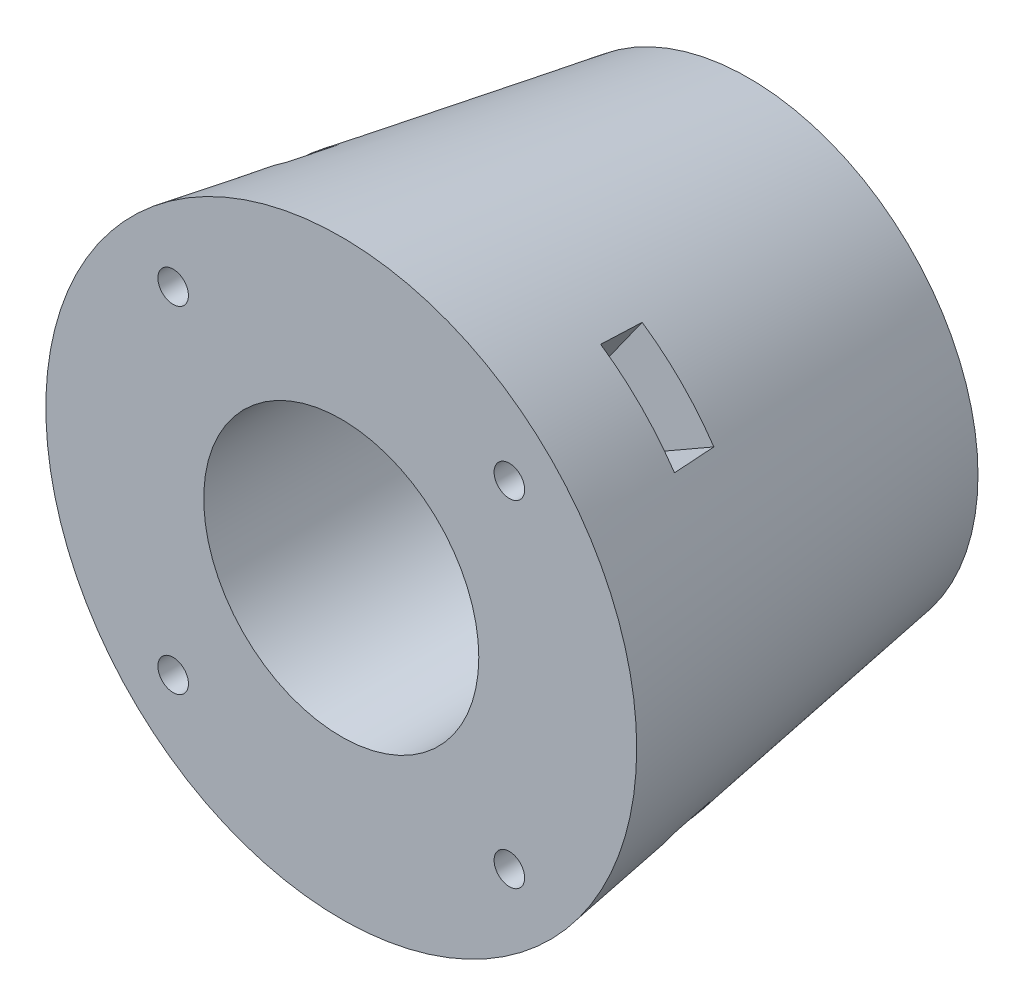
SolidWorks part; units mm, degrees
ref_plane "Front Plane" through (0, 0, 0) normal (0, 0, 1) x (1, 0, 0)
ref_plane "Top Plane" through (0, 0, 0) normal (0, 1, 0) x (1, 0, 0)
ref_plane "Right Plane" through (0, 0, 0) normal (1, 0, 0) x (0, 0, -1)
sketch "Sketch1" plane through (0, 0, 0) normal (0, 0, 1) x (1, 0, 0)
  line L0 (0, 88.1643) -> (0, -104.4147) construction
  line L1 (-136.2458, 0) -> (150.1972, 0) construction
  circle A0 centre (0, 0) radius 29
  dimension "D1" = 58
extrude "Boss-Extrude1" add sketch "Sketch1" against normal blind 40 draft 9.23
sketch "Sketch2" plane through (0, 0, 0) normal (0, 0, 1) x (1, 0, 0)
  line L0 (0, 30.1683) -> (0, -32.48) construction
  line L1 (-34.7918, 0) -> (41.1876, 0) construction
  line L2 (-34.7918, -16.5) -> (41.1876, -16.5) construction
  line L3 (-34.7918, 16.5) -> (41.1876, 16.5) construction
  line L4 (-16.5, 30.1683) -> (-16.5, -32.48) construction
  line L5 (16.5, 30.1683) -> (16.5, -32.48) construction
  circle A0 centre (-16.5, 16.5) radius 1.5
  circle A1 centre (16.5, 16.5) radius 1.5
  circle A2 centre (16.5, -16.5) radius 1.5
  circle A3 centre (-16.5, -16.5) radius 1.5
  dimension "D1" = 3
extrude "Cut-Extrude1" cut sketch "Sketch2" against normal blind 10
ref_plane "Plane1" through (0, 0, -10) normal (0, 0, 1) x (1, 0, 0)
sketch "Sketch4" plane through (0, 0, 0) normal (0, 0, 1) x (1, 0, 0)
  circle A0 centre (0, 0) radius 13.5
  dimension "D1" = 27
extrude "Cut-Extrude3" cut sketch "Sketch4" against normal blind 35
sketch "Sketch5" plane through (0, 0, -35) normal (0, 0, 1) x (1, 0, 0)
  circle A0 centre (0, 0) radius 7 construction
  circle A1 centre (7, 0) radius 1.6
  circle A2 centre (-3.5, -6.0622) radius 1.6
  circle A3 centre (-3.5, 6.0622) radius 1.6
  point P11 (0, 0)
  dimension "D1" = 14
  dimension "D2" = 3.2
  dimension "D3" = 3
extrude "Cut-Extrude4" cut sketch "Sketch5" against normal blind 35
ref_plane "Plane2" through (0, 0, -10) normal (0, 0, 1) x (1, 0, 0)
sketch "Sketch6" plane through (0, 0, -10) normal (0, 0, 1) x (1, 0, 0)
  line L0 (0, 33.7018) -> (0, -35.9968) construction
  line L1 (-40.6717, 0) -> (42.2017, 0) construction
  line L2 (11.6689, 17.2752) -> (17.7614, 25.8107)
  line L3 (17.0272, 12.0279) -> (26.1483, 17.2605)
  line L4 (12.0279, -17.0272) -> (17.2605, -26.1483)
  line L5 (17.2752, -11.6689) -> (25.8107, -17.7614)
  line L6 (-17.0272, -12.0279) -> (-26.1483, -17.2605)
  line L7 (-11.6689, -17.2752) -> (-17.7614, -25.8107)
  line L8 (-12.0279, 17.0272) -> (-17.2605, 26.1483)
  line L9 (-17.2752, 11.6689) -> (-25.8107, 17.7614)
  arc A0 (11.6689, 17.2752) -> (17.0272, 12.0279) centre (0, 0) cw
  arc A1 (17.7614, 25.8107) -> (26.1483, 17.2605) centre (0, 0) cw
  arc A2 (25.8107, -17.7614) -> (17.2605, -26.1483) centre (0, 0) cw
  arc A3 (17.2752, -11.6689) -> (12.0279, -17.0272) centre (0, 0) cw
  arc A4 (-17.7614, -25.8107) -> (-26.1483, -17.2605) centre (0, 0) cw
  arc A5 (-11.6689, -17.2752) -> (-17.0272, -12.0279) centre (0, 0) cw
  arc A6 (-25.8107, 17.7614) -> (-17.2605, 26.1483) centre (0, 0) cw
  arc A7 (-17.2752, 11.6689) -> (-12.0279, 17.0272) centre (0, 0) cw
  point P24 (0, 0)
  dimension "D1" = 4
extrude "Cut-Extrude5" cut sketch "Sketch6" against normal blind 4.5
